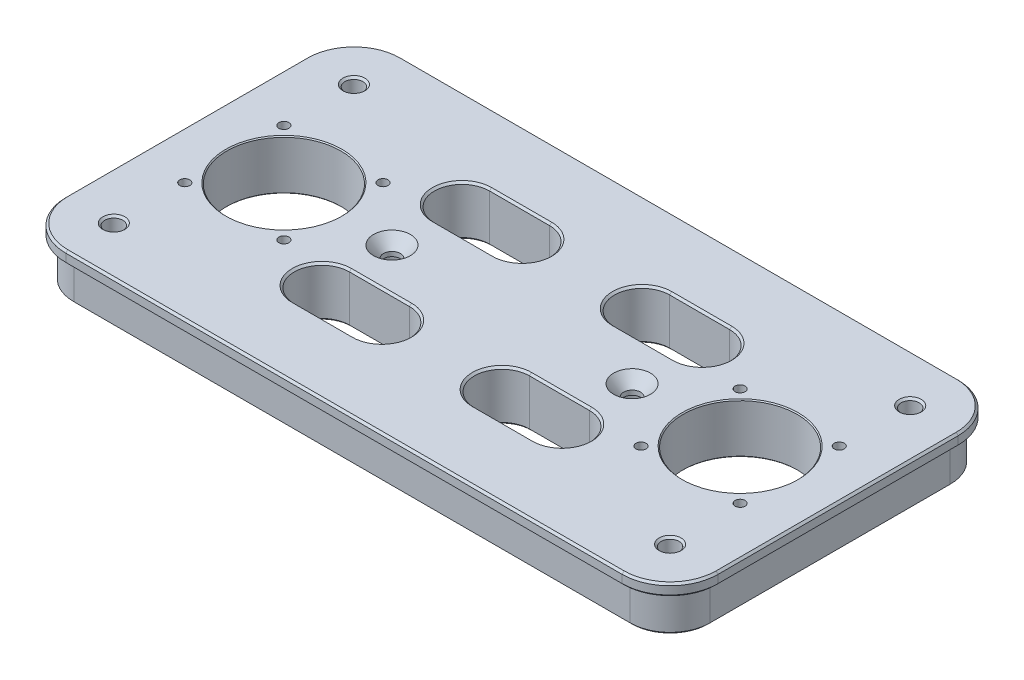
SolidWorks part; units mm, degrees
material "6061-T6 Aluminum"
ref_plane "Front Plane" through (0, 0, 0) normal (0, 0, 1) x (1, 0, 0)
ref_plane "Top Plane" through (0, 0, 0) normal (0, 1, 0) x (1, 0, 0)
ref_plane "Right Plane" through (0, 0, 0) normal (1, 0, 0) x (0, 0, -1)
sketch "Sketch1" plane through (0, 0, 0) normal (0, 1, 0) x (1, 0, 0)
  line L1 (-159, -80) -> (159, -80)
  line L2 (-159, -80) -> (-159, 80)
  line L3 (-159, 80) -> (159, 80)
  line L4 (159, -80) -> (159, 80)
  line L5 (-159, -80) -> (159, 80) construction
  line L6 (-159, 80) -> (159, -80) construction
  point P0 (0, 0)
  dimension "D1" = 160
  dimension "D2" = 318
extrude "Boss-Extrude1" add sketch "Sketch1" along normal blind 25
sketch "Sketch2" plane through (0, 25, 0) normal (0, 1, 0) x (1, 0, 0)
  line L0 (-114, 0) -> (0, 0) construction
  line L1 (0, 0) -> (114, 0) construction
  circle A0 centre (-114, 0) radius 28.5
  circle A1 centre (114, 0) radius 28.5
  dimension "D1" = 228
  dimension "D2" = 57
extrude "Cut-Extrude1" cut sketch "Sketch2" against normal through all
sketch "Sketch4" plane through (0, 25, 0) normal (0, 1, 0) x (1, 0, 0)
  line L0 (60, 0) -> (0, 0) construction
  line L1 (0, 0) -> (-60, 0) construction
  circle A0 centre (-60, 0) radius 9.55
  circle A1 centre (60, 0) radius 9.55
  dimension "D1" = 19.1
  dimension "D2" = 120
extrude "Cut-Extrude2" cut sketch "Sketch4" against normal through all both and the other way through all
chamfer "Chamfer1" distance 0.5 angle 45 8 edges at (114, 25, 28.5) (114, 0, 28.5) (60, 25, -9.55) (60, 0, 9.55) (-60, 25, -9.55) (-60, 0, 9.55) (-114, 25, 28.5) (-114, 0, 28.5)
fillet "Fillet1" radius 20 4 edges at (159, 12.5, 80) (159, 12.5, -80) (-159, 12.5, -80) (-159, 12.5, 80)
hole_wizard "M8 Clearance Hole1" positions "Sketch5" profile "Sketch6" hole size "M8" standard "ANSI Metric" end condition through all
sketch "Sketch5" plane through (0, 0, 0) normal (0, 1, 0) x (1, 0, 0)
  point P0 (-139, 60)
  point P3 (-139, -60)
  point P6 (139, 60)
  point P9 (139, -60)
sketch "Sketch6" plane through (-139, 0, -60) normal (1, 0, 0) x (0, 0, -1)
  line L0 (0, 0) -> (0, 25)
  line L1 (0, 25) -> (4.5, 25)
  line L2 (4.5, 25) -> (4.5, 0)
  line L5 (4.5, 0) -> (0, 0)
  line L11 (0, -6.35) -> (0, 107.95) construction
  dimension "Thru Hole Dia." = 9
  dimension "Thru Hole Depth" = 25
sketch "Sketch7" plane through (0, 0, 0) normal (0, -1, 0) x (1, 0, 0)
  line L1 (89.235, 24.765) -> (138.765, 24.765) construction
  line L2 (89.235, 24.765) -> (89.235, -24.765) construction
  line L3 (89.235, -24.765) -> (138.765, -24.765) construction
  line L4 (138.765, 24.765) -> (138.765, -24.765) construction
  line L5 (89.235, 24.765) -> (138.765, -24.765) construction
  line L6 (89.235, -24.765) -> (138.765, 24.765) construction
  line L7 (-138.765, 24.765) -> (-89.235, 24.765) construction
  line L8 (-138.765, 24.765) -> (-138.765, -24.765) construction
  line L9 (-138.765, -24.765) -> (-89.235, -24.765) construction
  line L10 (-89.235, 24.765) -> (-89.235, -24.765) construction
  line L11 (-138.765, 24.765) -> (-89.235, -24.765) construction
  line L12 (-138.765, -24.765) -> (-89.235, 24.765) construction
  circle A0 centre (89.235, 24.765) radius 3.302 construction
  circle A1 centre (138.765, -24.765) radius 3.302 construction
  circle A2 centre (138.765, 24.765) radius 3.302 construction
  circle A3 centre (89.235, -24.765) radius 3.302 construction
  circle A4 centre (89.235, 24.765) radius 3.302
  circle A5 centre (138.765, -24.765) radius 3.302
  circle A6 centre (138.765, 24.765) radius 3.302
  circle A7 centre (89.235, -24.765) radius 3.302
  circle A12 centre (-138.765, -24.765) radius 3.302
  circle A13 centre (-89.235, -24.765) radius 3.302
  circle A14 centre (-89.235, 24.765) radius 3.302
  circle A15 centre (-138.765, 24.765) radius 3.302
  point P13 (114, 0)
  point P15 (-114, 0)
hole_wizard "M6x1.0 Tapped Hole1" positions "Sketch8" profile "Sketch9" tap size "M6x1.0" standard "ANSI Metric" end condition through all
sketch "Sketch8" plane through (0, 0, 0) normal (0, -1, 0) x (-1, 0, 0)
  point P0 (138.765, -24.765)
  point P3 (89.235, -24.765)
  point P6 (89.235, 24.765)
  point P9 (138.765, 24.765)
  point P12 (-89.235, -24.765)
  point P15 (-138.765, -24.765)
  point P18 (-89.235, 24.765)
  point P21 (-138.765, 24.765)
cosmetic thread "Hole Thread11" parameters "D2"=6
cosmetic thread "Hole Thread12" parameters "D2"=6
cosmetic thread "Hole Thread13" parameters "D2"=6
cosmetic thread "Hole Thread14" parameters "D2"=6
cosmetic thread "Hole Thread16" parameters "D2"=6
sketch "Sketch9" plane through (-138.765, 0, 24.765) normal (1, 0, 0) x (0, 0, -1)
  line L0 (0, 0) -> (0, 25)
  line L1 (0, 25) -> (2.5, 25)
  line L2 (2.5, 25) -> (2.5, 0)
  line L5 (2.5, 0) -> (0, 0)
  line L11 (0, -6.35) -> (0, 107.95) construction
  dimension "Thru Tap Drill Dia." = 5
  dimension "Thru Tap Drill Depth" = 25
cosmetic thread "Hole Thread17" parameters "D2"=6
cosmetic thread "Hole Thread18" parameters "D2"=6
cosmetic thread "Hole Thread19" parameters "D2"=6
sketch "Sketch13" plane through (0, 25, 0) normal (0, 1, 0) x (1, 0, 0)
  circle A0 centre (60, 0) radius 13.411
  circle A1 centre (-60, 0) radius 14.7245
extrude "Boss-Extrude3" add sketch "Sketch13" against normal blind 8
hole_wizard "CSK for 5/16 Flat Head Socket Cap Screw1" positions "Sketch14" profile "Sketch15" countersink size "5/16" standard "ANSI Inch" end condition through all
sketch "Sketch14" plane through (0, 25, 0) normal (0, 1, 0) x (1, 0, 0)
  point P0 (60, 0)
  point P3 (-60, 0)
sketch "Sketch15" plane through (60, 25, 0) normal (1, 0, 0) x (0, 0, 1)
  line L0 (0, 0) -> (0, 25)
  line L1 (0, 25) -> (4.2164, 25)
  line L2 (4.2164, 25) -> (4.2164, 5.7335)
  line L3 (4.2164, 5.7335) -> (9.2005, 0)
  line L5 (9.2005, 0) -> (0, 0)
  line L6 (-4.2164, 5.7335) -> (-9.2005, 0) construction
  line L11 (0, -6.35) -> (0, 107.95) construction
  dimension "Thru Hole Dia." = 8.4328
  dimension "Thru Hole Depth" = 25
  dimension "Near C'Sink Dia." = 18.401
  dimension "Near C'Sink Angle" = 82
sketch "Sketch16" plane through (0, 25, 0) normal (0, -1, 0) x (1, 0, 0)
  line L4 (159, 60) -> (159, -60) construction
  line L5 (139, -80) -> (-139, -80) construction
  line L6 (-159, -60) -> (-159, 60) construction
  line L7 (-139, 80) -> (139, 80) construction
  line L8 (163, -60) -> (163, 60)
  line L9 (139, 84) -> (-139, 84)
  line L10 (-163, 60) -> (-163, -60)
  line L11 (-139, -84) -> (139, -84)
  line L12 (163, -60) -> (163, 60)
  line L13 (139, 84) -> (-139, 84)
  line L14 (-163, 60) -> (-163, -60)
  line L15 (-139, -84) -> (139, -84)
  line L16 (159, 60) -> (159, -60)
  line L17 (139, -80) -> (-139, -80)
  line L18 (-159, -60) -> (-159, 60)
  line L19 (-139, 80) -> (139, 80)
  arc A4 (159, 60) -> (139, 80) centre (139, 60) ccw construction
  arc A5 (139, -80) -> (159, -60) centre (139, -60) ccw construction
  arc A6 (-159, -60) -> (-139, -80) centre (-139, -60) ccw construction
  arc A7 (-139, 80) -> (-159, 60) centre (-139, 60) ccw construction
  arc A8 (163, 60) -> (139, 84) centre (139, 60) ccw
  arc A9 (-139, 84) -> (-163, 60) centre (-139, 60) ccw
  arc A10 (-163, -60) -> (-139, -84) centre (-139, -60) ccw
  arc A11 (139, -84) -> (163, -60) centre (139, -60) ccw
  arc A12 (163, 60) -> (139, 84) centre (139, 60) ccw
  arc A13 (-139, 84) -> (-163, 60) centre (-139, 60) ccw
  arc A14 (-163, -60) -> (-139, -84) centre (-139, -60) ccw
  arc A15 (139, -84) -> (163, -60) centre (139, -60) ccw
  arc A16 (159, 60) -> (139, 80) centre (139, 60) ccw
  arc A17 (139, -80) -> (159, -60) centre (139, -60) ccw
  arc A18 (-159, -60) -> (-139, -80) centre (-139, -60) ccw
  arc A19 (-139, 80) -> (-159, 60) centre (-139, 60) ccw
  dimension "D1" = 4
extrude "Boss-Extrude4" add sketch "Sketch16" along normal blind 6
sketch "Sketch17" plane through (0, 0, 0) normal (0, -1, 0) x (1, 0, 0)
  line L0 (-60, -35.0192) -> (-30, -35.0192) construction
  line L1 (-60, -21.2373) -> (-30, -21.2373)
  line L2 (-60, -48.8012) -> (-30, -48.8012)
  circle A0 centre (-60, -35.0192) radius 9.2363 construction
  arc A1 (-69.9426, -40.7596) -> (-50.0574, -40.7596) centre (-60, -35.0192) ccw construction
  arc A2 (-60, -21.2373) -> (-60, -48.8012) centre (-60, -35.0192) ccw
  arc A3 (-30, -48.8012) -> (-30, -21.2373) centre (-30, -35.0192) ccw
  point P2 (-45, -35.0192)
  point P11 (-60, -21.2373)
  dimension "D1" = 30
extrude "Cut-Extrude3" cut sketch "Sketch17" against normal through all
sketch "Sketch18" plane through (0, 0, 0) normal (0, -1, 0) x (1, 0, 0)
  circle A8 centre (-105, -70) radius 3.25
  circle A9 centre (-75, -70) radius 3.25
  circle A10 centre (-45, -70) radius 3.25
  circle A11 centre (-15, -70) radius 3.25
  circle A12 centre (15, -70) radius 3.25
  circle A13 centre (45, -70) radius 3.25
  circle A14 centre (75, -70) radius 3.25
  circle A15 centre (105, -70) radius 3.25
  circle A24 centre (-105, 70) radius 3.25
  circle A25 centre (-75, 70) radius 3.25
  circle A26 centre (-45, 70) radius 3.25
  circle A27 centre (-15, 70) radius 3.25
  circle A28 centre (15, 70) radius 3.25
  circle A29 centre (45, 70) radius 3.25
  circle A30 centre (75, 70) radius 3.25
  circle A31 centre (105, 70) radius 3.25
hole_wizard "M6x1.0 Tapped Hole2" positions "Sketch19" profile "Sketch20" tap size "M6x1.0" standard "ANSI Metric"
sketch "Sketch19" plane through (0, 0, 0) normal (0, -1, 0) x (-1, 0, 0)
  point P1 (-75, 70)
  point P4 (-45, 70)
  point P7 (-105, 70)
  point P10 (-15, 70)
  point P13 (15, 70)
  point P16 (45, 70)
  point P19 (75, 70)
  point P22 (105, 70)
  point P25 (-105, -70)
  point P28 (-75, -70)
  point P31 (-45, -70)
  point P34 (-15, -70)
  point P37 (15, -70)
  point P40 (45, -70)
  point P43 (75, -70)
  point P46 (105, -70)
sketch "Sketch20" plane through (75, 0, -70) normal (1, 0, 0) x (0, 0, -1)
  line L0 (0, 0) -> (0, 16.5022)
  line L1 (0, 16.5022) -> (2.5, 15)
  line L2 (2.5, 15) -> (2.5, 0)
  line L5 (2.5, 0) -> (0, 0)
  line L10 (0, 16.5022) -> (-2.5, 15) construction
  line L11 (0, -6.35) -> (0, 107.95) construction
  dimension "Tap Drill Dia." = 5
  dimension "Tap Drill Depth" = 15
  dimension "Drill Angle" = 118
cosmetic thread "Hole Thread20" parameters "D1"=12, "D2"=6
cosmetic thread "Hole Thread21" parameters "D1"=12, "D2"=6
cosmetic thread "Hole Thread22" parameters "D1"=12, "D2"=6
cosmetic thread "Hole Thread23" parameters "D1"=12, "D2"=6
cosmetic thread "Hole Thread24" parameters "D1"=12, "D2"=6
cosmetic thread "Hole Thread25" parameters "D1"=12, "D2"=6
cosmetic thread "Hole Thread26" parameters "D1"=12, "D2"=6
cosmetic thread "Hole Thread27" parameters "D1"=12, "D2"=6
cosmetic thread "Hole Thread28" parameters "D1"=12, "D2"=6
cosmetic thread "Hole Thread29" parameters "D1"=12, "D2"=6
cosmetic thread "Hole Thread30" parameters "D1"=12, "D2"=6
cosmetic thread "Hole Thread31" parameters "D1"=12, "D2"=6
cosmetic thread "Hole Thread32" parameters "D1"=12, "D2"=6
cosmetic thread "Hole Thread33" parameters "D1"=12, "D2"=6
cosmetic thread "Hole Thread34" parameters "D1"=12, "D2"=6
cosmetic thread "Hole Thread35" parameters "D1"=12, "D2"=6
mirror "Mirror1" about plane through (0, 0, 0) normal (1, 0, 0) of "Cut-Extrude3"
mirror "Mirror2" about plane through (0, 0, 0) normal (0, 0, 1) of "Mirror1", "Cut-Extrude3"
chamfer "Chamfer4" distance 1 angle 45 64 edges at (139, 0, -64.5) (139, 25, -64.5) (-139, 0, -64.5) (-139, 25, -64.5) (139, 0, 55.5) (139, 25, 55.5) (-139, 0, 55.5) (-139, 25, 55.5) (0, 19, -84) (155.9706, 19, -76.9706) (-155.9706, 19, -76.9706) (163, 19, 0) (-163, 19, 0) (155.9706, 19, 76.9706) (-155.9706, 19, 76.9706) (0, 19, 84) (0, 25, -84) (155.9706, 25, -76.9706) (-155.9706, 25, -76.9706) (163, 25, 0) (-163, 25, 0) (155.9706, 25, 76.9706) (-155.9706, 25, 76.9706) (0, 25, 84) (-45, 25, -21.2373) (-73.7819, 25, -35.0192) (-16.2181, 25, -35.0192) (-45, 25, -48.8012) (-45, 0, -21.2373) (-73.7819, 0, -35.0192) (-16.2181, 0, -35.0192) (-45, 0, -48.8012) (0, 0, -80) (-153.1421, 0, -74.1421) (153.1421, 0, -74.1421) (-159, 0, 0) (159, 0, 0) (-153.1421, 0, 74.1421) (153.1421, 0, 74.1421) (0, 0, 80) (45, 25, -48.8012) (16.2181, 25, -35.0192) (73.7819, 25, -35.0192) (45, 25, -21.2373) (45, 0, -48.8012) (16.2181, 0, -35.0192) (73.7819, 0, -35.0192) (45, 0, -21.2373) (45, 25, 21.2373) (73.7819, 25, 35.0192) (16.2181, 25, 35.0192) (45, 25, 48.8012) (45, 0, 21.2373) (73.7819, 0, 35.0192) (16.2181, 0, 35.0192) (45, 0, 48.8012) (-45, 25, 21.2373) (-73.7819, 25, 35.0192) (-16.2181, 25, 35.0192) (-45, 25, 48.8012) (-45, 0, 21.2373) (-73.7819, 0, 35.0192) (-16.2181, 0, 35.0192) (-45, 0, 48.8012)
